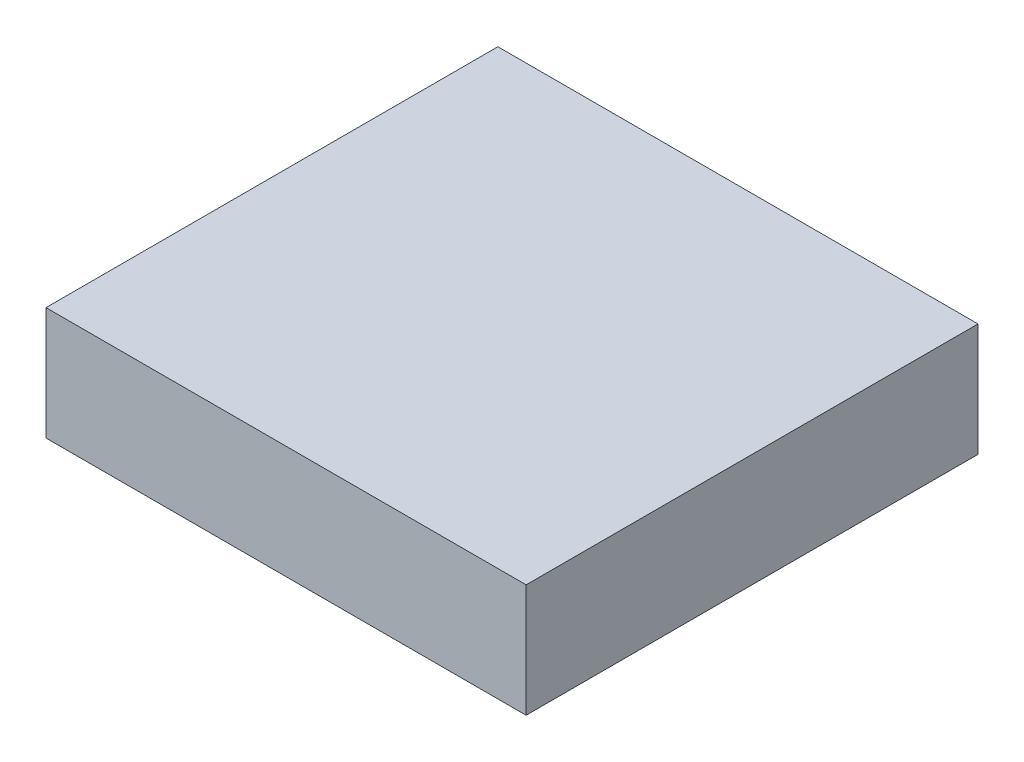
SolidWorks part; units mm, degrees
ref_plane "Plano frontal" through (0, 0, 0) normal (0, 0, 1) x (1, 0, 0)
ref_plane "Plano superior" through (0, 0, 0) normal (0, 1, 0) x (1, 0, 0)
ref_plane "Plano direito" through (0, 0, 0) normal (1, 0, 0) x (0, 0, -1)
sketch "Esboço2" plane through (0, 0, 0) normal (0, 1, 0) x (1, 0, 0)
  line L1 (25.5, -24) -> (-25.5, -24)
  line L2 (25.5, -24) -> (25.5, 24)
  line L3 (25.5, 24) -> (-25.5, 24)
  line L4 (-25.5, -24) -> (-25.5, 24)
  line L5 (25.5, -24) -> (-25.5, 24) construction
  line L6 (25.5, 24) -> (-25.5, -24) construction
  point P0 (0, 0)
  dimension "D1" = 48
  dimension "D2" = 51
extrude "Ressalto-extrusão1" add sketch "Esboço2" along normal blind 12
